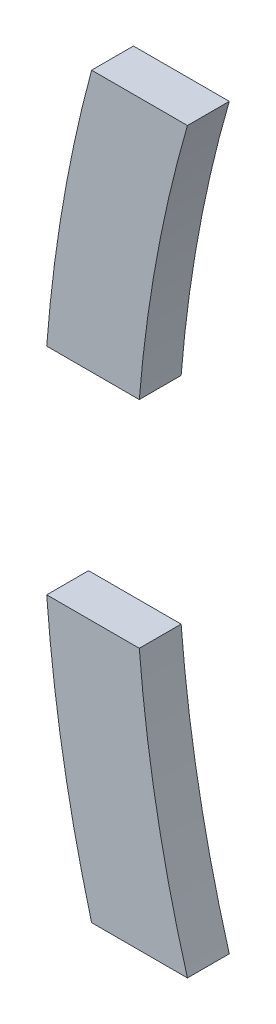
SolidWorks part; units mm, degrees
ref_plane "Front Plane" through (0, 0, 0) normal (0, 0, 1) x (1, 0, 0)
ref_plane "Top Plane" through (0, 0, 0) normal (0, 1, 0) x (1, 0, 0)
ref_plane "Right Plane" through (0, 0, 0) normal (1, 0, 0) x (0, 0, -1)
sketch "Sketch1" plane through (0, 0, 0) normal (0, 0, 1) x (1, 0, 0)
  line L0 (-517.4695, 241.3) -> (0, 0) construction
  line L1 (0, 0) -> (-584.2, 0) construction
  line L2 (0, 0) -> (-517.4695, -241.3) construction
  line L3 (-517.4695, 241.3) -> (-494.9347, 230.7918)
  line L4 (-494.9347, -230.7918) -> (-517.4695, -241.3)
  line L5 (-565.0697, 9.525) -> (-565.0697, -9.525) construction
  line L6 (-531.0673, 193.2927) -> (0, 0) construction
  line L7 (0, 0) -> (-531.0673, -193.2927) construction
  line L8 (-517.4695, 241.3) -> (-532.0375, 241.3)
  line L9 (-644.9589, 196.85) -> (-186.7772, 196.85) construction
  line L10 (-517.4695, -241.3) -> (-532.0375, -241.3)
  line L13 (-51.4198, -196.85) -> (-644.9589, -196.85) construction
  arc A0 (-532.0375, 241.3) -> (-532.0375, -241.3) centre (0, 0) ccw
  arc A1 (-494.9347, 230.7918) -> (-494.9347, -230.7918) centre (0, 0) ccw
  circle A2 centre (-565.0697, 9.525) radius 3.175
  circle A3 centre (-565.0697, -9.525) radius 3.175
  circle A4 centre (-526.1215, 206.375) radius 3.175
  circle A5 centre (-533.2015, 187.325) radius 3.175
  circle A6 centre (-526.1215, -206.375) radius 3.175
  circle A7 centre (-533.2015, -187.325) radius 3.175
  circle A8 centre (0, 0) radius 565.15 construction
  dimension "D1" = 1168.4
  dimension "D2" = 1092.2
  dimension "D6" = 6.35
  dimension "D9" = 6.35
  dimension "D12" = 6.35
  dimension "D14" = 1130.3
  dimension "D19" = 44.45
  dimension "D3" = 25
  dimension "D4" = 25
  dimension "D5" = 19.05
  dimension "D7" = 196.85
  dimension "D8" = 19.05
  dimension "D10" = 196.85
  dimension "D11" = 19.05
  dimension "D13" = 9.525
  dimension "D15" = 9.525
  dimension "D16" = 9.525
  dimension "D17" = 5
  dimension "D18" = 5
  dimension "D20" = 44.45
extrude "Boss-Extrude1" add sketch "Sketch1" along normal blind 17.272
sketch "Sketch2" plane through (0, 0, 17.272) normal (0, 0, 1) x (1, 0, 0)
  line L4 (-595.2426, 44.45) -> (-544.288, 44.45)
  line L5 (-595.2426, -44.45) -> (-544.288, -44.45)
  line L6 (0, 0) -> (-584.2, 0) construction
  line L7 (0, -196.85) -> (-752.9087, -196.85) construction
  line L8 (0, 196.85) -> (-702.1976, 196.85) construction
  line L9 (-543.1014, -247.65) -> (-486.7183, -247.65)
  line L10 (-577.1168, -152.4) -> (-524.4039, -152.4)
  line L11 (-543.1014, 247.65) -> (-486.7183, 247.65)
  line L12 (-577.1168, 152.4) -> (-524.4039, 152.4)
  circle A0 centre (0, 0) radius 596.9 construction
  arc A1 (-494.9347, 230.7918) -> (-494.9347, -230.7918) centre (0, 0) ccw construction
  arc A2 (-494.9347, 230.7918) -> (-486.7183, 247.65) centre (0, 0) ccw
  arc A5 (-595.2426, 44.45) -> (-595.2426, -44.45) centre (0, 0) ccw
  arc A7 (-543.1014, -247.65) -> (-577.1168, -152.4) centre (0, 0) cw
  arc A9 (-543.1014, 247.65) -> (-577.1168, 152.4) centre (0, 0) ccw
  arc A11 (-486.7183, -247.65) -> (-524.4039, -152.4) centre (0, 0) cw
  arc A12 (-544.288, 44.45) -> (-544.288, -44.45) centre (0, 0) ccw
  arc A13 (-524.4039, 152.4) -> (-486.7183, 247.65) centre (0, 0) cw
  circle M22 centre (-526.1215, -206.375) radius 3.175
  circle M23 centre (-526.1215, 206.375) radius 3.175
  circle M24 centre (-533.2015, 187.325) radius 3.175
  circle M25 centre (-565.0697, 9.525) radius 3.175
  arc M26 (-494.9347, -230.7918) -> (-494.9347, 230.7918) centre (0, 0) cw
  circle M30 centre (-565.0697, -9.525) radius 3.175
  circle M33 centre (-533.2015, -187.325) radius 3.175
  dimension "D1" = 1193.8
  dimension "D10" = 546.1
  dimension "D11" = 546.1
  dimension "D2" = 44.45
  dimension "D3" = 44.45
  dimension "D4" = 196.85
  dimension "D5" = 196.85
  dimension "D6" = 44.45
  dimension "D7" = 50.8
  dimension "D8" = 44.45
  dimension "D9" = 50.8
extrude "Cut-Extrude1" cut sketch "Sketch2" against normal up to surface (17.272 mm away) contours A7 L9 L10 M26 M33 M22 | L4 A5 L5 M26 M30 M25 | L11 A9 L12 M26 M23 M24 up to face at (-532.0352, 0, 0)
